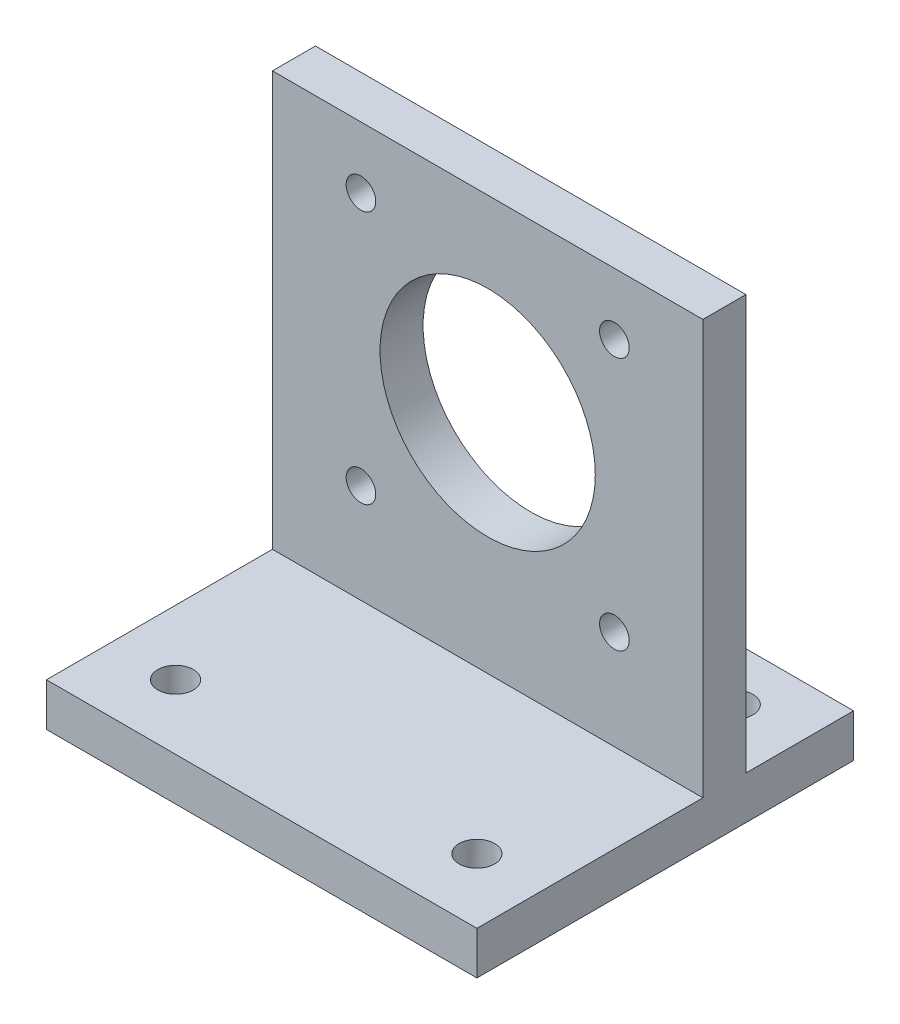
SolidWorks part; units mm, degrees
material "6061-T6 (SS)"
ref_plane "Front Plane" through (0, 0, 0) normal (0, 0, 1) x (1, 0, 0)
ref_plane "Top Plane" through (0, 0, 0) normal (0, 1, 0) x (1, 0, 0)
ref_plane "Right Plane" through (0, 0, 0) normal (1, 0, 0) x (0, 0, -1)
sketch "Sketch1" plane through (0, 0, 0) normal (0, 0, 1) x (1, 0, 0)
  line L1 (-40, -50) -> (40, -50)
  line L2 (-40, -50) -> (-40, 35)
  line L3 (-40, 35) -> (40, 35)
  line L4 (40, -50) -> (40, 35)
  circle A0 centre (0, 0) radius 20
  circle A1 centre (-23.55, -23.55) radius 2.75
  circle A2 centre (-23.55, 23.55) radius 2.75
  circle A3 centre (23.55, -23.55) radius 2.75
  circle A4 centre (23.55, 23.55) radius 2.75
extrude "Front_Plate" add sketch "Sketch1" along normal blind 8
sketch "Sketch2" plane through (0, 0, 0) normal (0, 0, 1) x (1, 0, 0)
  line L1 (-40, -50) -> (40, -50)
  line L2 (-40, -50) -> (-40, -42)
  line L3 (-40, -42) -> (40, -42)
  line L4 (40, -50) -> (40, -42)
extrude "Bench_Foot" add sketch "Sketch2" along normal blind 70 from offset 20
sketch "Sketch3" plane through (0, 0, 0) normal (0, 1, 0) x (1, 0, 0)
  circle A0 centre (-28, 10) radius 3.3
  circle A1 centre (-28, -38) radius 3.3
  circle A2 centre (28, 10) radius 3.3
  circle A3 centre (28, -38) radius 3.3
extrude "Four_M6_Foot_Clearances" cut sketch "Sketch3" against normal through all and the other way through all
